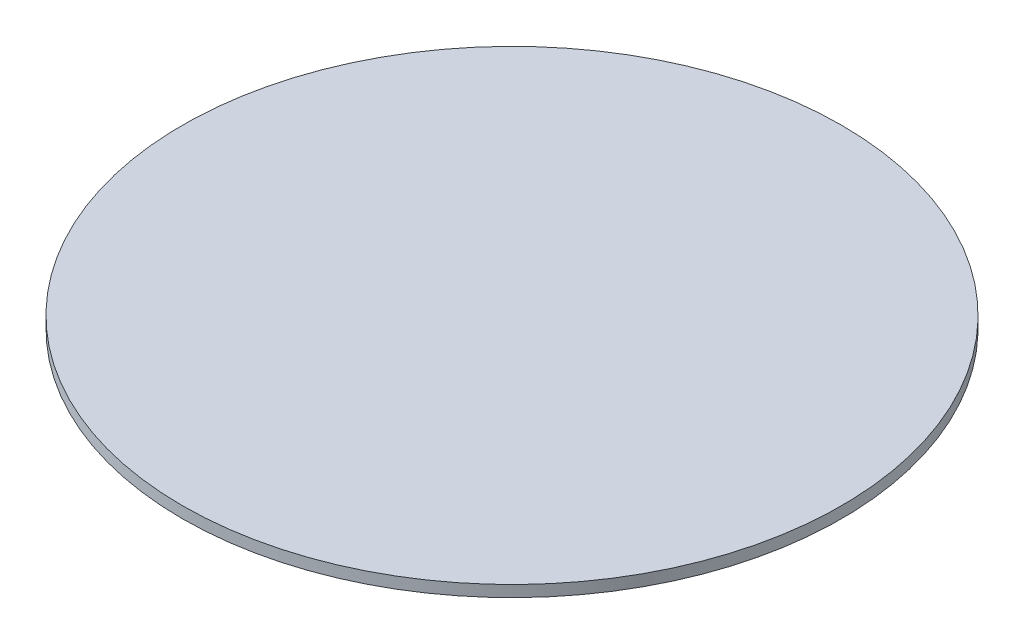
SolidWorks part; units mm, degrees
ref_plane "前视基准面" through (0, 0, 0) normal (0, 0, 1) x (1, 0, 0)
ref_plane "上视基准面" through (0, 0, 0) normal (0, 1, 0) x (1, 0, 0)
ref_plane "右视基准面" through (0, 0, 0) normal (1, 0, 0) x (0, 0, -1)
sketch "草图1" plane through (0, 0, 0) normal (0, 1, 0) x (1, 0, 0)
  circle A0 centre (0, 0) radius 145
  dimension "D1" = 290
extrude "凸台-拉伸1" add sketch "草图1" along normal blind 5
sketch "草图2" plane through (0, 5, 0) normal (0, 1, 0) x (1, 0, 0)
  circle A0 centre (0, 0) radius 132 construction
  circle A1 centre (18.7856, -130.6564) radius 8
  circle A2 centre (-18.7856, -130.6564) radius 8
  circle A3 centre (-54.8348, -120.0714) radius 8
  circle A4 centre (-86.4416, -99.7589) radius 8
  circle A5 centre (-111.0455, -71.3646) radius 8
  circle A6 centre (-126.6531, -37.1887) radius 8
  circle A7 centre (-132, 0) radius 8
  circle A8 centre (-126.6531, 37.1887) radius 8
  circle A9 centre (-111.0455, 71.3646) radius 8
  circle A10 centre (-86.4416, 99.7589) radius 8
  circle A11 centre (-54.8348, 120.0714) radius 8
  circle A12 centre (-18.7856, 130.6564) radius 8
  circle A13 centre (18.7856, 130.6564) radius 8
  circle A14 centre (54.8348, 120.0714) radius 8
  circle A15 centre (86.4416, 99.7589) radius 8
  circle A16 centre (111.0455, 71.3646) radius 8
  circle A17 centre (126.6531, 37.1887) radius 8
  circle A18 centre (132, 0) radius 8
  circle A19 centre (126.6531, -37.1887) radius 8
  circle A20 centre (111.0455, -71.3646) radius 8
  circle A21 centre (86.4416, -99.7589) radius 8
  circle A22 centre (54.8348, -120.0714) radius 8
  dimension "D1" = 264
  dimension "D2" = 16
  dimension "D3" = 22
sketch "草图3" plane through (0, 5, 0) normal (0, 1, 0) x (1, 0, 0)
  line L0 (0, -68) -> (0, 0) construction
  circle A0 centre (0, 0) radius 102 construction
  circle A1 centre (0, -102) radius 10
  circle A2 centre (-31.5197, -97.0078) radius 10
  circle A17 centre (0, 0) radius 68 construction
  circle A18 centre (15.1314, -66.2951) radius 10
  circle A19 centre (-15.1314, -66.2951) radius 10
  circle A30 centre (0, 0) radius 34 construction
  circle A31 centre (-34, 0) radius 10
  circle A32 centre (-17, 29.4449) radius 10
  circle A33 centre (17, 29.4449) radius 10
  circle A34 centre (34, 0) radius 10
  circle A35 centre (17, -29.4449) radius 10
  circle A36 centre (-17, -29.4449) radius 10
  circle A37 centre (0, 0) radius 10
  circle A41 centre (-42.3973, -53.1645) radius 10
  circle A42 centre (-61.2659, -29.5041) radius 10
  circle A43 centre (-68, 0) radius 10
  circle A44 centre (-61.2659, 29.5041) radius 10
  circle A45 centre (-42.3973, 53.1645) radius 10
  circle A46 centre (-15.1314, 66.2951) radius 10
  circle A47 centre (15.1314, 66.2951) radius 10
  circle A48 centre (42.3973, 53.1645) radius 10
  circle A49 centre (61.2659, 29.5041) radius 10
  circle A50 centre (68, 0) radius 10
  circle A51 centre (-59.9541, -82.5197) radius 10
  circle A52 centre (-82.5197, -59.9541) radius 10
  circle A53 centre (-97.0078, -31.5197) radius 10
  circle A54 centre (-102, 0) radius 10
  circle A55 centre (-97.0078, 31.5197) radius 10
  circle A56 centre (-82.5197, 59.9541) radius 10
  circle A57 centre (-59.9541, 82.5197) radius 10
  circle A58 centre (-31.5197, 97.0078) radius 10
  circle A59 centre (0, 102) radius 10
  circle A60 centre (31.5197, 97.0078) radius 10
  circle A61 centre (59.9541, 82.5197) radius 10
  circle A62 centre (82.5197, 59.9541) radius 10
  circle A63 centre (97.0078, 31.5197) radius 10
  circle A64 centre (102, 0) radius 10
  circle A65 centre (97.0078, -31.5197) radius 10
  circle A66 centre (82.5197, -59.9541) radius 10
  circle A71 centre (61.2659, -29.5041) radius 10
  circle A72 centre (42.3973, -53.1645) radius 10
  circle A73 centre (59.9541, -82.5197) radius 10
  circle A74 centre (31.5197, -97.0078) radius 10
  dimension "D1" = 204
  dimension "D2" = 20
  dimension "D4" = 136
  dimension "D6" = 68
  dimension "D3" = 20
  dimension "D5" = 14
  dimension "D7" = 6
